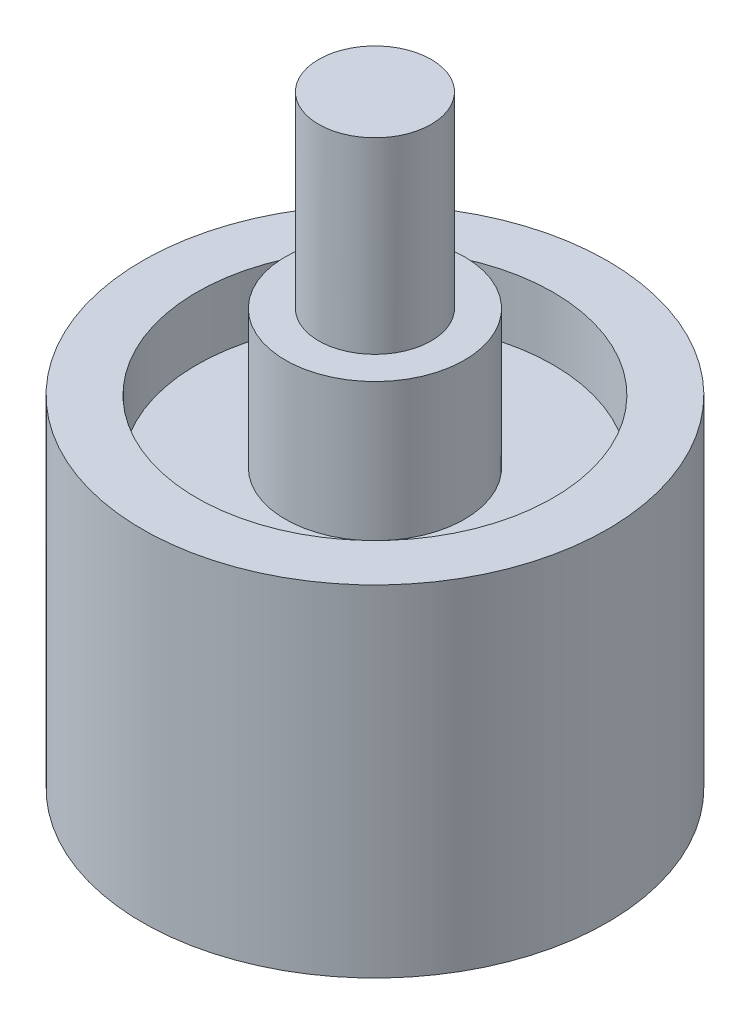
SolidWorks part; units mm, degrees
ref_plane "Front Plane" through (0, 0, 0) normal (0, 0, 1) x (1, 0, 0)
ref_plane "Top Plane" through (0, 0, 0) normal (0, 1, 0) x (1, 0, 0)
ref_plane "Right Plane" through (0, 0, 0) normal (1, 0, 0) x (0, 0, -1)
sketch "Sketch1" plane through (0, 0, 0) normal (0, 1, 0) x (1, 0, 0)
  circle A0 centre (0, 0) radius 3
extrude "Boss-Extrude1" add sketch "Sketch1" along normal blind 10
sketch "Sketch2" plane through (0, 0, 0) normal (0, -1, 0) x (1, 0, 0)
  circle A0 centre (0, 0) radius 4.775
extrude "Boss-Extrude2" add sketch "Sketch2" along normal blind 10.35
sketch "Sketch3" plane through (0, -10.35, 0) normal (0, -1, 0) x (1, 0, 0)
  circle A0 centre (0, 0) radius 9.5
  dimension "D1" = 19
extrude "Boss-Extrude3" add sketch "Sketch3" along normal blind 3 and the other way blind 3
sketch "Sketch4" plane through (0, -13.35, 0) normal (0, -1, 0) x (1, 0, 0)
  circle A0 centre (0, 0) radius 9.5
  circle A1 centre (0, 0) radius 12.4
extrude "Boss-Extrude4" add sketch "Sketch4" against normal offset from surface (9.35 mm away) 4 up to face at (0, 0, -3)
sketch "Sketch5" plane through (0, -13.35, 0) normal (0, -1, 0) x (1, 0, 0)
  circle A1 centre (0, 0) radius 12.4
  circle A2 centre (0, 0) radius 12.4
  circle A3 centre (0, 0) radius 9.5
  circle A4 centre (0, 0) radius 9.5
  dimension "D1" = 0
  dimension "D2" = 0
extrude "Boss-Extrude5" add sketch "Sketch5" along normal blind 8.8
